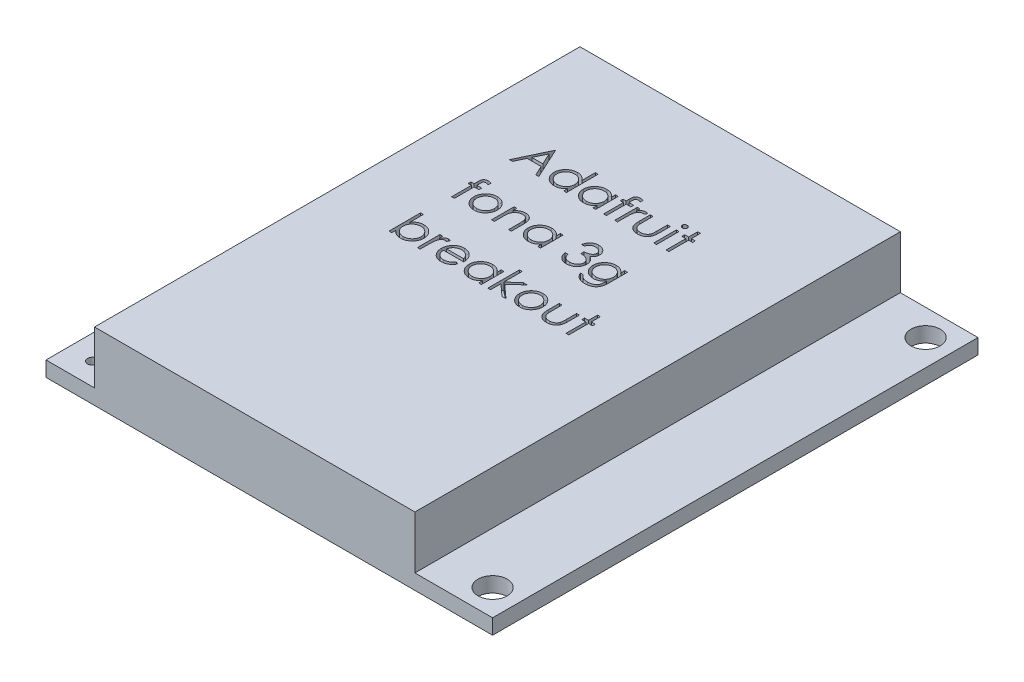
SolidWorks part; units mm, degrees
ref_plane "Front Plane" through (0, 0, 0) normal (0, 0, 1) x (1, 0, 0)
ref_plane "Top Plane" through (0, 0, 0) normal (0, 1, 0) x (1, 0, 0)
ref_plane "Right Plane" through (0, 0, 0) normal (1, 0, 0) x (0, 0, -1)
sketch "Sketch1" plane through (0, 0, 0) normal (0, 1, 0) x (1, 0, 0)
  line L1 (-23, -25) -> (23, -25)
  line L2 (-23, -25) -> (-23, 25)
  line L3 (-23, 25) -> (23, 25)
  line L4 (23, -25) -> (23, 25)
  line L5 (-23, -25) -> (23, 25) construction
  line L6 (-23, 25) -> (23, -25) construction
  point P0 (0, 0)
  dimension "D1" = 46
  dimension "D2" = 50
extrude "Boss-Extrude1" add sketch "Sketch1" along normal blind 7
hole_wizard "Ø3.0mm Dowel Hole1" positions "Sketch3" profile "Sketch4" hole size "Ø3.0" standard "ANSI Metric" end condition through all
sketch "Sketch3" plane through (0, 7, 0) normal (0, 1, 0) x (1, 0, 0)
  line L0 (23, -25) -> (23, 25) construction
  line L1 (23, 25) -> (-23, 25) construction
  line L2 (-23, -25) -> (23, -25) construction
  point P0 (20.3, 22.3)
  point P4 (20.3, -22.3)
  point P10 (0, 0)
  point P13 (0, 0)
  point P16 (0, 0)
  dimension "D1" = 2.7
  dimension "D2" = 2.7
  dimension "D3" = 2.7
sketch "Sketch4" plane through (20.3, 7, -22.3) normal (1, 0, 0) x (0, 0, 1)
  line L0 (0, 0) -> (0, 7)
  line L1 (0, 7) -> (1.5, 7)
  line L2 (1.5, 7) -> (1.5, 0)
  line L5 (1.5, 0) -> (0, 0)
  line L11 (0, -6.35) -> (0, 107.95) construction
  dimension "Thru Hole Dia." = 3
  dimension "Thru Hole Depth" = 7
hole_wizard "Ø1.0mm Dowel Hole1" positions "Sketch5" profile "Sketch6" hole size "Ø1.0" standard "ANSI Metric" end condition through all
sketch "Sketch5" plane through (0, 7, 0) normal (0, 1, 0) x (1, 0, 0)
  line L0 (-23, 25) -> (-23, -25) construction
  line L1 (23, 25) -> (-23, 25) construction
  point P0 (-20.5, 23)
  dimension "D1" = 2.5
  dimension "D2" = 2
sketch "Sketch6" plane through (-20.5, 7, -23) normal (1, 0, 0) x (0, 0, 1)
  line L0 (0, 0) -> (0, 7)
  line L1 (0, 7) -> (0.5, 7)
  line L2 (0.5, 7) -> (0.5, 0)
  line L5 (0.5, 0) -> (0, 0)
  line L11 (0, -6.35) -> (0, 107.95) construction
  dimension "Thru Hole Dia." = 1
  dimension "Thru Hole Depth" = 7
pattern_linear "LPattern1" count 19 spacing 2.54 along (0, 0, 1) of "Ø1.0mm Dowel Hole1"
sketch "Sketch7" plane through (0, 7, 0) normal (0, 1, 0) x (1, 0, 0)
  line L0 (-23, -25) -> (23, -25) construction
  line L1 (-23, 25) -> (-18, 25)
  line L2 (-23, 25) -> (-23, -25)
  line L3 (-23, -25) -> (-18, -25)
  line L4 (-18, 25) -> (-18, -25)
  line L6 (23, 25) -> (15, 25)
  line L7 (23, 25) -> (23, -25)
  line L8 (23, -25) -> (15, -25)
  line L9 (15, 25) -> (15, -25)
  dimension "D1" = 5
  dimension "D2" = 8
extrude "Cut-Extrude1" cut sketch "Sketch7" against normal blind 5.44
sketch "Sketch8" plane through (0, 7, 0) normal (0, 1, 0) x (1, 0, 0)
  text T0 "Adafruit \r\nfona 3g\r\nbreakout"
extrude "Cut-Extrude2" cut sketch "Sketch8" against normal blind 1
